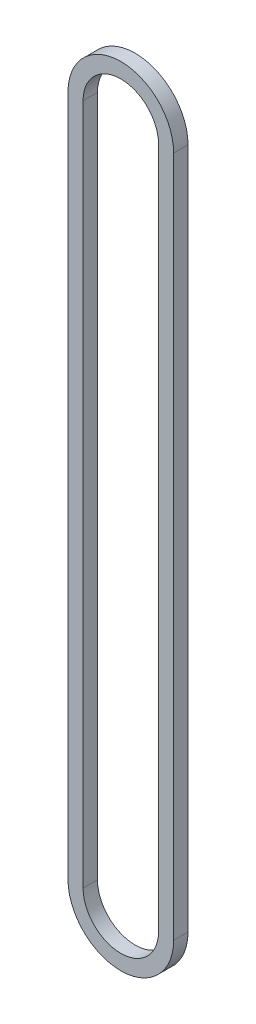
SolidWorks part; units mm, degrees
ref_plane "Front Plane" through (0, 0, 0) normal (0, 0, 1) x (1, 0, 0)
ref_plane "Top Plane" through (0, 0, 0) normal (0, 1, 0) x (1, 0, 0)
ref_plane "Right Plane" through (0, 0, 0) normal (1, 0, 0) x (0, 0, -1)
sketch "Sketch1" plane through (0, 0, 0) normal (0, 0, 1) x (1, 0, 0)
  line L0 (0, 90.3354) -> (0, -90.3354) construction
  line L1 (14, 90.3354) -> (14, -90.3354)
  line L2 (-14, 90.3354) -> (-14, -90.3354)
  line L3 (0, -90.3354) -> (0, 90.3354) construction
  line L4 (-10, -90.3354) -> (-10, 90.3354)
  line L5 (10, -90.3354) -> (10, 90.3354)
  arc A0 (14, 90.3354) -> (-14, 90.3354) centre (0, 90.3354) ccw
  arc A1 (-14, -90.3354) -> (14, -90.3354) centre (0, -90.3354) ccw
  arc A2 (-10, -90.3354) -> (10, -90.3354) centre (0, -90.3354) ccw
  arc A3 (10, 90.3354) -> (-10, 90.3354) centre (0, 90.3354) ccw
  point P2 (0, 0)
  point P10 (0, 0)
  point P15 (0, -80)
  point P16 (0, -80)
  point P17 (0, -92.7375)
  point P18 (0, 0)
  point P19 (0, -87.9379)
  point P20 (0, 0)
  point P21 (0, -90.3354)
  dimension "D2" = 20
  dimension "D3" = 28
extrude "Boss-Extrude1" add sketch "Sketch1" along normal blind 3.81
